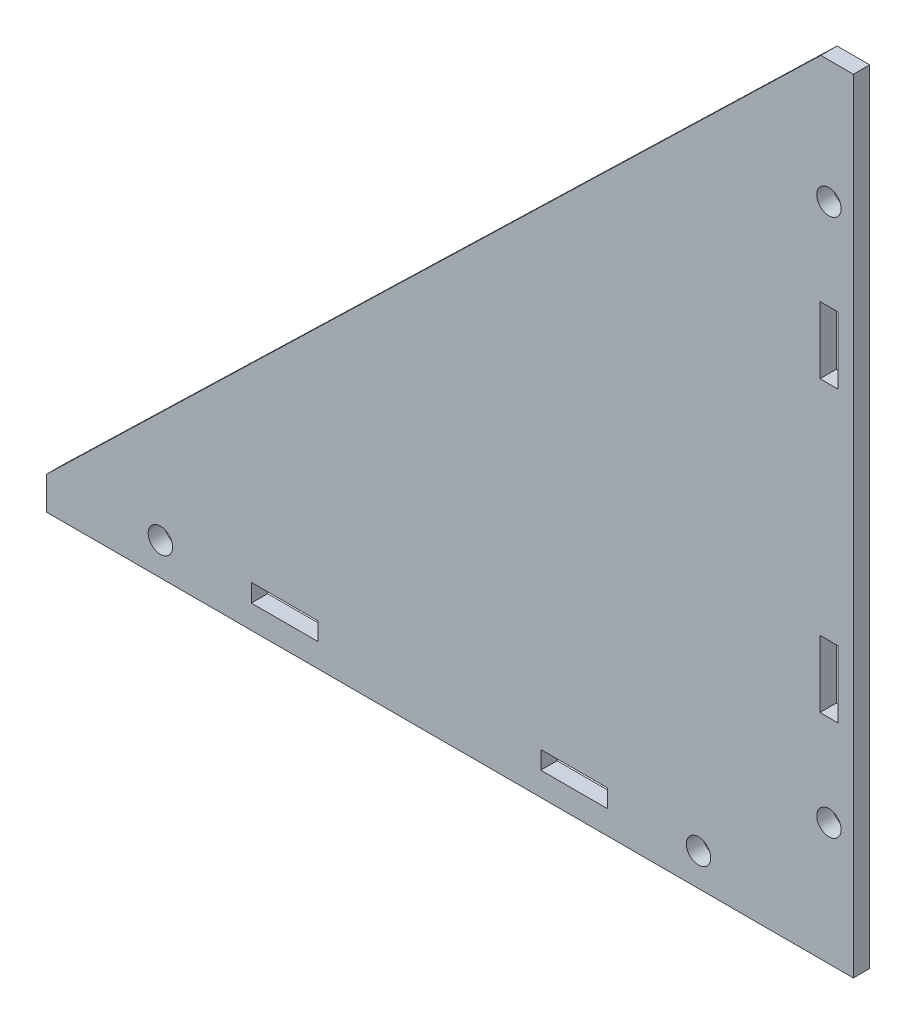
SolidWorks part; units mm, degrees
ref_plane "前视基准面" through (0, 0, 0) normal (0, 0, 1) x (1, 0, 0)
ref_plane "上视基准面" through (0, 0, 0) normal (0, 1, 0) x (1, 0, 0)
ref_plane "右视基准面" through (0, 0, 0) normal (1, 0, 0) x (0, 0, -1)
sketch "草图1" plane through (0, 0, 0) normal (0, 0, 1) x (1, 0, 0)
  line L1 (-24.1162, -115.6745) -> (-15.9162, -115.6745)
  line L2 (-15.9162, -113.4745) -> (-15.9162, -115.6745)
  line L3 (-24.1162, -113.4745) -> (-15.9162, -113.4745)
  line L4 (-24.1162, -113.4745) -> (-24.1162, -115.6745)
  line L5 (19.5838, -113.4745) -> (19.5838, -115.6745)
  line L6 (19.5838, -113.4745) -> (11.3838, -113.4745)
  line L7 (11.3838, -113.4745) -> (11.3838, -115.6745)
  line L10 (19.5838, -115.6745) -> (11.3838, -115.6745)
  line L29 (44.7338, -118.5745) -> (48.7338, -118.5745)
  line L38 (-35.2662, -114.5745) -> (-24.1162, -114.5745) construction
  line L60 (11.3838, -114.5745) -> (-15.9162, -114.5745) construction
  line L61 (-2.2662, -114.5745) -> (-2.2662, -99.1509) construction
  line L64 (47.8338, -92.4245) -> (47.8338, -84.2245)
  line L65 (45.6338, -84.2245) -> (47.8338, -84.2245)
  line L66 (19.5838, -114.5745) -> (30.7338, -114.5745) construction
  line L107 (-3.2662, -118.5745) -> (44.7338, -118.5745)
  line L111 (45.6338, -92.4245) -> (45.6338, -84.2245)
  line L112 (45.6338, -92.4245) -> (47.8338, -92.4245)
  line L113 (45.6338, -48.7662) -> (47.8338, -48.7662)
  line L114 (45.6338, -48.7662) -> (45.6338, -56.9662)
  line L115 (45.6338, -56.9662) -> (47.8338, -56.9662)
  line L116 (47.8338, -48.7662) -> (47.8338, -56.9662)
  line L118 (46.7338, -103.5745) -> (46.7338, -92.4245) construction
  line L119 (46.7338, -56.9662) -> (46.7338, -84.2245) construction
  line L120 (46.7338, -70.5953) -> (31.3131, -70.2741) construction
  line L121 (46.7338, -48.7662) -> (46.7338, -37.6162) construction
  line L124 (-49.2662, -118.5745) -> (-3.2662, -118.5745)
  line L126 (48.7338, -118.5745) -> (49.7338, -118.5745)
  line L127 (49.7338, -118.5745) -> (49.7338, -22.5745)
  line L129 (-49.2662, -114.5745) -> (-49.2662, -118.5745)
  line L130 (49.7338, -22.5745) -> (45.7338, -22.5745)
  line L131 (45.7338, -22.5745) -> (-49.2662, -114.5745)
  circle A0 centre (-35.2662, -114.5745) radius 1.5
  circle A1 centre (30.7338, -114.5745) radius 1.5
  circle A3 centre (46.7338, -103.5745) radius 1.5
  circle A4 centre (46.7338, -37.6162) radius 1.5
extrude "凸台-拉伸1" add sketch "草图1" along normal blind 2
